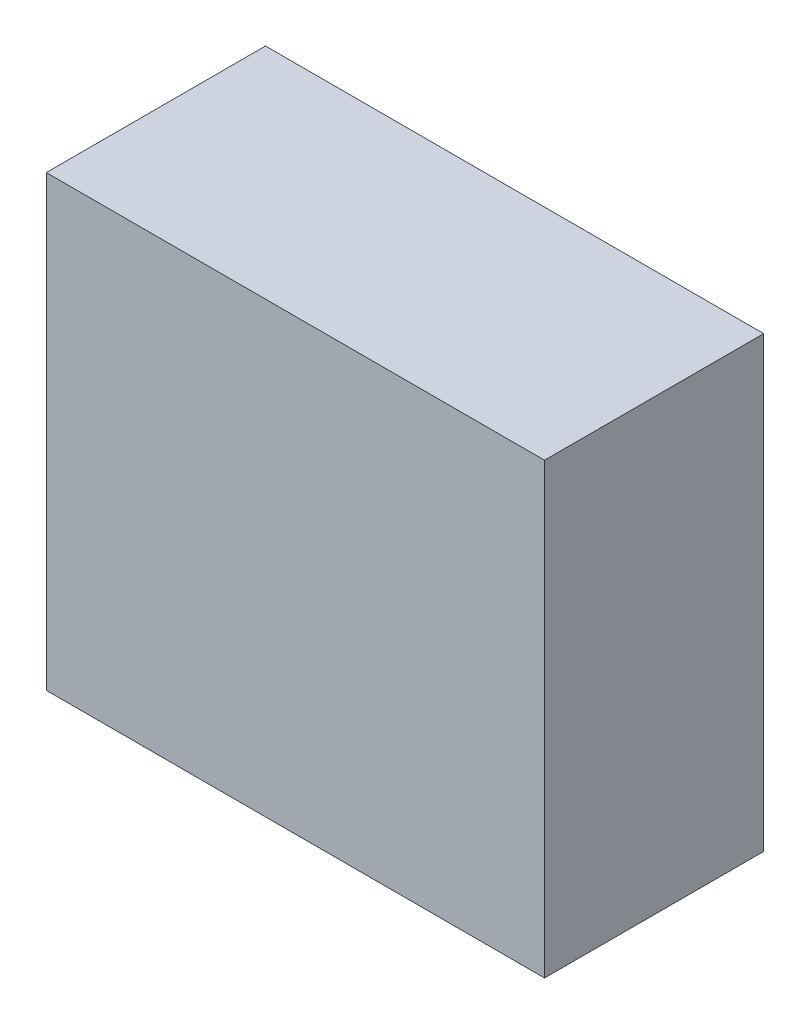
SolidWorks part; units mm, degrees
ref_plane "Front Plane" through (0, 0, 0) normal (0, 0, 1) x (1, 0, 0)
ref_plane "Top Plane" through (0, 0, 0) normal (0, 1, 0) x (1, 0, 0)
ref_plane "Right Plane" through (0, 0, 0) normal (1, 0, 0) x (0, 0, -1)
sketch "Sketch1" plane through (0, 0, 0) normal (0, 0, 1) x (1, 0, 0)
  line L1 (0, 0) -> (100, 0)
  line L2 (0, 0) -> (0, 90)
  line L3 (0, 90) -> (100, 90)
  line L4 (100, 0) -> (100, 90)
  dimension "D1" = 100
  dimension "D2" = 90
extrude "Profile" add sketch "Sketch1" along normal blind 44
equation "\"Profile_Depth\"= 44mm"
equation "\"D1@Profile\" = \"Profile_Depth\""
equation "\"Profile_Sketch_1\"= 100mm"
equation "\"D1@Sketch1\" = \"Profile_Sketch_1\""
equation "\"Profile_Sketch_2\"= 90mm"
equation "\"D2@Sketch1\" = \"Profile_Sketch_2\""
equation "\"EnvelopeWidth\"= 100mm"
equation "\"EnvelopeHeight\"= 90mm"
